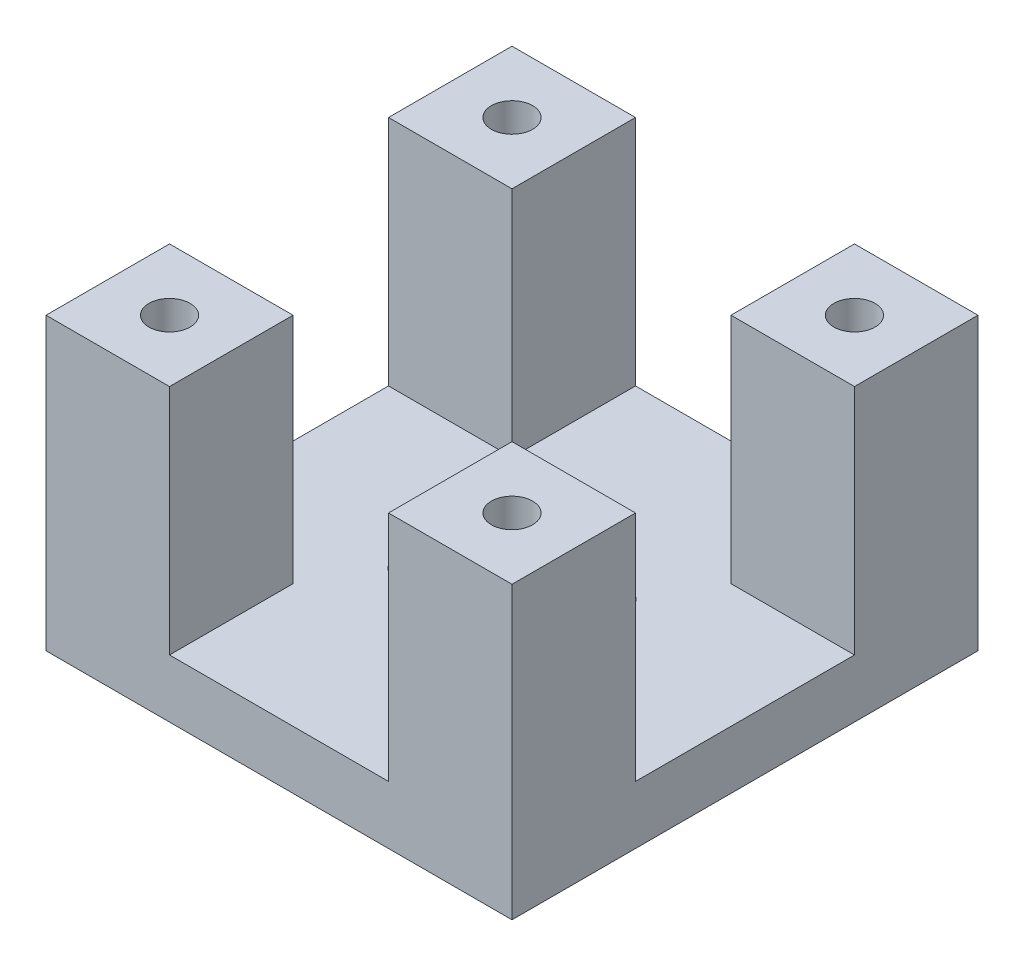
SolidWorks part; units mm, degrees
material "1060 Alloy"
ref_plane "Front" through (0, 0, 0) normal (0, 0, 1) x (1, 0, 0)
ref_plane "Top" through (0, 0, 0) normal (0, 1, 0) x (1, 0, 0)
ref_plane "Right" through (0, 0, 0) normal (1, 0, 0) x (0, 0, -1)
sketch "Sketch1" plane through (0, 0, 0) normal (0, 1, 0) x (1, 0, 0)
  line L0 (0, 0) -> (0, 86.5638) construction
  line L1 (0, 0) -> (68.5951, 68.5951) construction
  line L2 (0, 0) -> (0, 15) construction
  line L3 (0, 0) -> (35.3553, 35.3553) construction
  line L5 (-48.1053, 48.1053) -> (48.1053, 48.1053)
  line L6 (-48.1053, 48.1053) -> (-48.1053, -48.1053)
  line L7 (-48.1053, -48.1053) -> (48.1053, -48.1053)
  line L8 (48.1053, 48.1053) -> (48.1053, -48.1053)
  circle A0 centre (0, 0) radius 11
  circle A1 centre (0, 15) radius 2
  circle A2 centre (35.3553, 35.3553) radius 4.25
  circle A3 centre (12.9904, 7.5) radius 2
  circle A4 centre (12.9904, -7.5) radius 2
  circle A5 centre (0, -15) radius 2
  circle A6 centre (-12.9904, -7.5) radius 2
  circle A7 centre (-12.9904, 7.5) radius 2
  circle A8 centre (35.3553, -35.3553) radius 4.25
  circle A9 centre (-35.3553, -35.3553) radius 4.25
  circle A10 centre (-35.3553, 35.3553) radius 4.25
  dimension "D2" = 4
  dimension "D4" = 22
  dimension "D5" = 8.5
  dimension "D1" = 45
  dimension "D3" = 15
  dimension "D12" = 50
  dimension "D14" = 12.75
  dimension "D15" = 12.75
  dimension "D16" = 12.75
  dimension "D8" = 15
  dimension "D9" = 15
  dimension "D6" = 12.75
  dimension "D7" = 6
  dimension "D10" = 4
extrude "main body" add sketch "Sketch1" along normal blind 60
sketch "Sketch4" plane through (0, 60, 0) normal (0, 1, 0) x (1, 0, 0)
  line L0 (-48.1053, 48.1053) -> (48.1053, 48.1053) construction
  line L1 (-22.6053, 48.1053) -> (22.6053, 48.1053)
  line L2 (-22.6053, 48.1053) -> (-22.6053, 22.6053)
  line L3 (-22.6053, -48.1053) -> (22.6053, -48.1053)
  line L4 (22.6053, 48.1053) -> (22.6053, 22.6053)
  line L5 (-48.1053, -48.1053) -> (48.1053, -48.1053) construction
  line L6 (-48.1053, 48.1053) -> (-48.1053, -48.1053) construction
  line L7 (-48.1053, 22.6053) -> (-22.6053, 22.6053)
  line L8 (-48.1053, 22.6053) -> (-48.1053, -22.6053)
  line L9 (-48.1053, -22.6053) -> (-22.6053, -22.6053)
  line L10 (48.1053, 22.6053) -> (48.1053, -22.6053)
  line L11 (48.1053, 48.1053) -> (48.1053, -48.1053) construction
  line L12 (-22.6053, -22.6053) -> (-22.6053, -48.1053)
  line L13 (22.6053, 22.6053) -> (48.1053, 22.6053)
  line L14 (22.6053, -22.6053) -> (22.6053, -48.1053)
  line L15 (22.6053, -22.6053) -> (48.1053, -22.6053)
  dimension "D1" = 12.75
  dimension "D2" = 12.75
  dimension "D3" = 12.75
  dimension "D4" = 12.75
extrude "main mill cut" cut sketch "Sketch4" against normal blind 48
sketch "Sketch2" plane through (0, 60, 0) normal (0, 1, 0) x (1, 0, 0)
  circle A0 centre (12.9904, 7.5) radius 3.625
  circle A1 centre (0, 0) radius 5.4201 construction
  circle A2 centre (0, 15) radius 3.625
  circle A3 centre (12.9904, -7.5) radius 3.625
  circle A4 centre (0, -15) radius 3.625
  circle A5 centre (-12.9904, -7.5) radius 3.625
  circle A6 centre (-12.9904, 7.5) radius 3.625
  point P18 (0, 0)
  dimension "D1" = 7.25
extrude "motor mount bolt head countersink" cut sketch "Sketch2" against normal blind 54
equation "\"D1@Sketch2\" = \"motor mount to housing m4 head diameter\""
equation "\"D1@motor mount bolt head countersink\" = \"motor to housing distance\" - \"motor mount plate thickness\" + \"motor mount to housing m4 head depth\""
equation "\"D2@Sketch1\" = \"motor mount to housing m4 screw hole diamater\""
equation "\"D3@Sketch1\"=\"motor mount pattern diameter\"/2"
equation "\"D8@Sketch1\"=\"motor mount pattern diameter\"/2"
equation "\"D9@Sketch1\"=\"motor mount pattern diameter\"/2"
equation "\"D4@Sketch1\" = \"motor mount coupler shaft hole diameter\""
equation "\"D12@Sketch1\"= \"motor mount to housing m8 pattern diameter\" / 2"
equation "\"D6@Sketch1\" = \"motor mount to housing m8 screw post radius\""
equation "\"D14@Sketch1\" = \"motor mount to housing m8 screw post radius\""
equation "\"D15@Sketch1\" = \"motor mount to housing m8 screw post radius\""
equation "\"D16@Sketch1\" = \"motor mount to housing m8 screw post radius\""
equation "\"D5@Sketch1\" = \"motor mount to housing m8 screw hole diameter\""
equation "\"D1@Sketch4\" = \"motor mount to housing m8 screw post radius\""
equation "\"D2@Sketch4\" = \"motor mount to housing m8 screw post radius\""
equation "\"D3@Sketch4\" = \"motor mount to housing m8 screw post radius\""
equation "\"D4@Sketch4\" = \"motor mount to housing m8 screw post radius\""
equation "\"bearing OD\" = 20mm"
equation "\"bearing outer race thickness\"= 1mm"
equation "\"bearing ID\"= 10mm"
equation "\"bearing depth\"= 6mm"
equation "\"bearing inner race thickness\"= 1mm"
equation "\"seal OD\" = 20mm"
equation "\"seal ID\"= 8mm"
equation "\"seal depth\"= 6mm"
equation "\"impeller base outer diameter\"= 1.75in"
equation "\"impeller base outer thickness\"= 1mm"
equation "\"impeller base center thickness\"= 5mm"
equation "\"impeller number of vanes\"= 8"
equation "\"impeller vane outer height`\"= 4mm"
equation "\"impeller vane inner height\"= 8mm"
equation "\"impeller primary vane opening diamater\"= 10mm"
equation "\"impeller shaft bore size\"=4mm "
equation "\"impeller vane inner thickness\"= .75mm"
equation "\"impeller vane outer thickness\"= 1.5mm"
equation "\"impeller primary vane entrance angle\"= 20deg"
equation "\"impeller secondary vane entrance angle\"= 20deg"
equation "\"impeller secondary vane opening diameter\"= 10mm"
equation "\"motor to housing distance\"= 60mm"
equation "\"motor mount pattern diameter\"= 30mm"
equation "\"motor mount coupler shaft hole diameter\"= \"coupler shaft base diameter\"+ 4mm"
equation "\"motor mount to housing m8 screw hole diameter\"= 8.5mm"
equation "\"motor mount to housing m8 screw post radius\"= ( 3 * \"motor mount to housing m8 screw hole diameter\" ) / 2"
equation "\"motor mount to housing m8 pattern diameter\"= 100mm"
equation "\"motor mount to housing m4 screw hole diamater\"= 4mm"
equation "\"motor mount to housing m4 head diameter\"= 7.25mm"
equation "\"motor mount to housing m4 head depth\"= 4mm"
equation "\"motor mount plate thickness\"= 6mm + \"motor mount to housing m4 head depth\""
equation "\"housing bearing seat lip thickness\" = 2mm"
equation "\"housing base thickness\"= \"housing bearing seat lip thickness\" + \"seal depth\" + \"bearing depth\""
equation "\"housing top impeller vertical clearance\"= 1mm"
equation "\"housing top impeller horizontal clearance\"= 1mm"
equation "\"housing top impeller bottom clearance\"= 2mm"
equation "\"housing top impeller cavity height\"= \"housing top impeller bottom clearance\" + \"impeller base center thickness\" + \"impeller vane inner height\" + \"housing top impeller vertical clearance\""
equation "\"housing top impeller cavity diameter\"= 2 * \"housing top impeller horizontal clearance\" + \"impeller base outer diameter\""
equation "\"housing top impeller cavity tip height\"= \"housing top impeller bottom clearance\" + \"housing top impeller vertical clearance\" + \"impeller base outer thickness\" + \"impeller vane outer height\""
equation "\"housing top entrance OD\"= 20mm"
equation "\"housing top exit OD\"= 5mm"
equation "\"housing top o-ring channel height\"= 1.5mm"
equation "\"housing top o ring channel width\"= 1.5mm"
equation "\"housing top o-ring circumference\" = 250mm"
equation "\"housing top o-ring radius\" = (\"housing top o-ring circumference\")/(2*3.14)"
equation "\"housing top threaded inlet depth\"= 8mm"
equation "\"housing top total thickness\"= \"housing top threaded inlet depth\" + \"housing top impeller cavity height\""
equation "\"housing top total width\"= 10mm"
equation "\"housing top exit threaded diameter\"= 8mm"
equation "\"housing top exit threaded depth\"= 8mm"
equation "\"motor shaft pride\"= 32mm"
equation "\"motor shaft flat section length from tip\"= 25.7mm"
equation "\"motor shaft bore end clearance\"= 2mm"
equation "\"motor mount shaft hole depth\"= \"motor shaft pride\""
equation "\"coupler shaft set screw drill hole diameter\"= 6mm"
equation "\"coupler shaft set screw 1 distance\"= \"motor mount shaft hole depth\" / 3"
equation "\"coupler shaft set screw 2 distance\"= \"motor mount shaft hole depth\" * 4 / 5"
equation "\"coupler shaft motor shaft hole diameter\"= 8mm"
equation "\"coupler shaft base diameter\"= 18mm"
equation "\"coupler shaft base length\"= \"motor mount shaft hole depth\" + 10mm"
equation "\"coupler shaft second section diameter\"= \"bearing ID\" + \"bearing inner race thickness\" * 2"
equation "\"coupler shaft second section length\"= \"motor to housing distance\" -  \"coupler shaft base length\" - 2mm"
equation "\"coupler shaft third section diamater\"= \"bearing ID\""
equation "\"coupler shaft third section length\"= \"bearing depth\""
equation "\"coupler shaft seal section diameter\" = \"seal ID\""
equation "\"coupler shaft seal section length\" = \"housing base thickness\"+\"housing top impeller bottom clearance\"-\"bearing depth\""
equation "\"coupler shaft impeller section diameter\" = 6mm"
equation "\"coupler shaft impeller section length\" = \"impeller bolt surface height\"-.5mm"
equation "\"coupler shaft impeller screw hole diameter\" = \"motor mount to housing m4 screw hole diamater\""
equation "\"coupler shaft impeller screw hole depth\" = 10mm"
